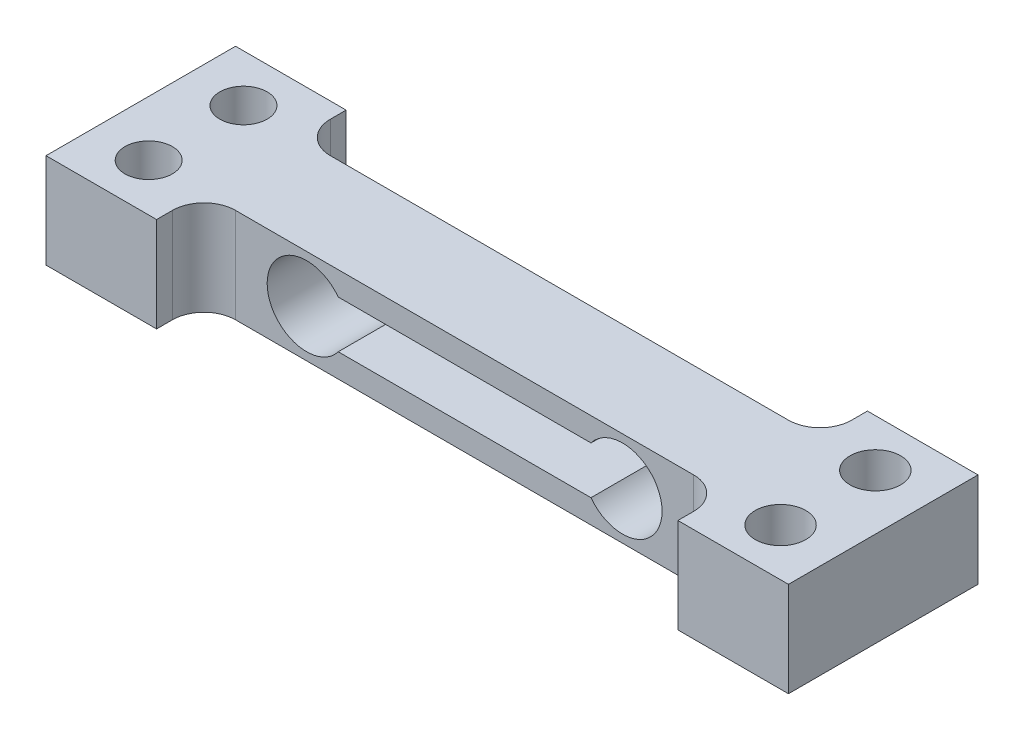
SolidWorks part; units mm, degrees
ref_plane "Front Plane" through (0, 0, 0) normal (0, 0, 1) x (1, 0, 0)
ref_plane "Top Plane" through (0, 0, 0) normal (0, 1, 0) x (1, 0, 0)
ref_plane "Right Plane" through (0, 0, 0) normal (1, 0, 0) x (0, 0, -1)
sketch "Sketch1" plane through (0, 0, 0) normal (0, 1, 0) x (1, 0, 0)
  line L0 (40, 0) -> (47, 0)
  line L13 (0, 0) -> (7, 0)
  line L14 (0, 0) -> (0, 12)
  line L15 (0, 12) -> (7, 12)
  line L16 (47, 0) -> (47, 12)
  line L18 (7, 0) -> (7, 1)
  line L19 (9, 3) -> (38, 3)
  line L20 (40, 0) -> (40, 1)
  line L22 (7, 12) -> (7, 11)
  line L23 (9, 9) -> (38, 9)
  line L24 (40, 12) -> (40, 11)
  line L25 (40, 12) -> (47, 12)
  circle A4 centre (3.5, 9) radius 1.5
  circle A5 centre (3.5, 3) radius 1.5
  circle A6 centre (43.5, 9) radius 1.6
  circle A7 centre (43.5, 3) radius 1.6
  arc A8 (7, 1) -> (9, 3) centre (9, 1) cw
  arc A9 (40, 1) -> (38, 3) centre (38, 1) ccw
  arc A10 (40, 11) -> (38, 9) centre (38, 11) cw
  arc A11 (7, 11) -> (9, 9) centre (9, 11) ccw
  dimension "D5" = 3.2
  dimension "D6" = 3
  dimension "D10" = 2
  dimension "D11" = 3
  dimension "D1" = 47
  dimension "D2" = 33
  dimension "D3" = 40
  dimension "D4" = 6
  dimension "D7" = 3.5
  dimension "D8" = 3.5
  dimension "D9" = 12
extrude "Boss-Extrude2" add sketch "Sketch1" along normal blind 6
sketch "Sketch2" plane through (0, 0, -9) normal (0, 0, -1) x (-1, 0, 0)
  line L0 (-23.5, 6) -> (-23.5, 0) construction
  line L1 (-38, 6) -> (-9, 6) construction
  line L2 (-38, 0) -> (-9, 0) construction
  line L3 (-33.5, 3) -> (-13.5, 3) construction
  line L4 (-23.5, 1.5) -> (-23.5, 4.5)
  line L6 (-31.5, 4.5) -> (-15.5, 4.5)
  line L8 (-31.5, 1.5) -> (-15.5, 1.5)
  arc A0 (-15.5, 1.5) -> (-15.5, 4.5) centre (-13.5, 3) ccw
  arc A1 (-31.5, 4.5) -> (-31.5, 1.5) centre (-33.5, 3) ccw
  point P9 (-23.5, 3)
  point P14 (-23.5, 3)
  dimension "D1" = 5
  dimension "D2" = 20
extrude "Cut-Extrude1" cut sketch "Sketch2" against normal through all contours A0 L6 A1 L8
